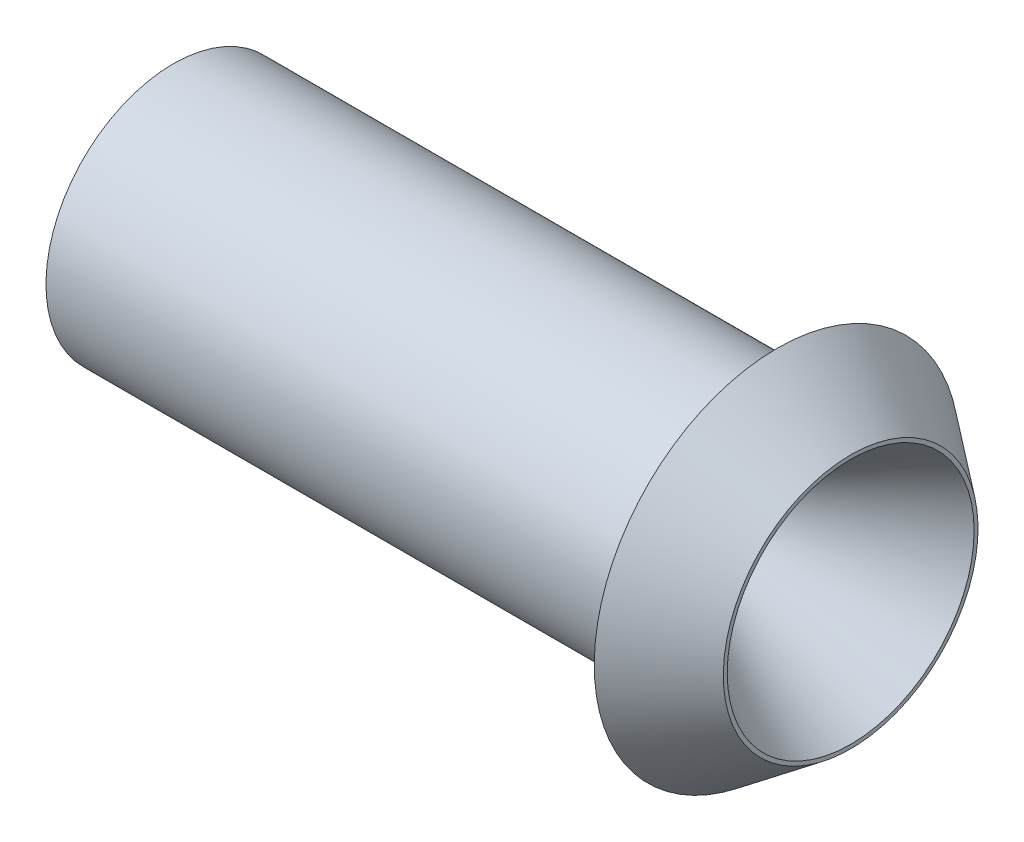
SolidWorks part; units mm, degrees
material "AISI 316 Annealed Stainless Steel Bar (SS)"
ref_plane "Front Plane" through (0, 0, 0) normal (0, 0, 1) x (1, 0, 0)
ref_plane "Top Plane" through (0, 0, 0) normal (0, 1, 0) x (1, 0, 0)
ref_plane "Right Plane" through (0, 0, 0) normal (1, 0, 0) x (0, 0, -1)
sketch "Sketch1" plane through (0, 0, 0) normal (0, 0, 1) x (1, 0, 0)
  line L0 (0, 0) -> (0, 8.255)
  line L1 (0, 8.255) -> (39.1302, 8.255)
  line L2 (39.1302, 8.255) -> (39.1302, 11.8491)
  line L3 (39.1302, 11.8491) -> (43.8997, 8.255)
  line L4 (43.8997, 8.255) -> (43.8997, 0)
  line L5 (43.8997, 0) -> (0, 0) construction
  line L7 (43.8997, 8.001) -> (33.9263, 2.2428)
  line L8 (33.9263, 2.2428) -> (32.6563, 2.2428)
  line L9 (32.6563, 2.2428) -> (0, 8.001)
  line L10 (0, 4.7625) -> (18.3664, 4.7625) construction
  line L11 (0, 3.175) -> (27.3696, 3.175) construction
  dimension "D1" = 16.51
  dimension "D2" = 39.1302
  dimension "D3" = 23.6982
  dimension "D4" = 37
  dimension "D5" = 0.254
  dimension "D6" = 0.254
  dimension "D7" = 30
  dimension "D8" = 32.6563
  dimension "ID" = 4.4856
  dimension "D9" = 1.27
  dimension "D10" = 10
  dimension "D11" = 3.175
  dimension "D12" = 4.7625
  dimension "D13" = 27.3696
  dimension "D14" = 18.3664
revolve "Revolve1" add sketch "Sketch1" angle 360 about L5
